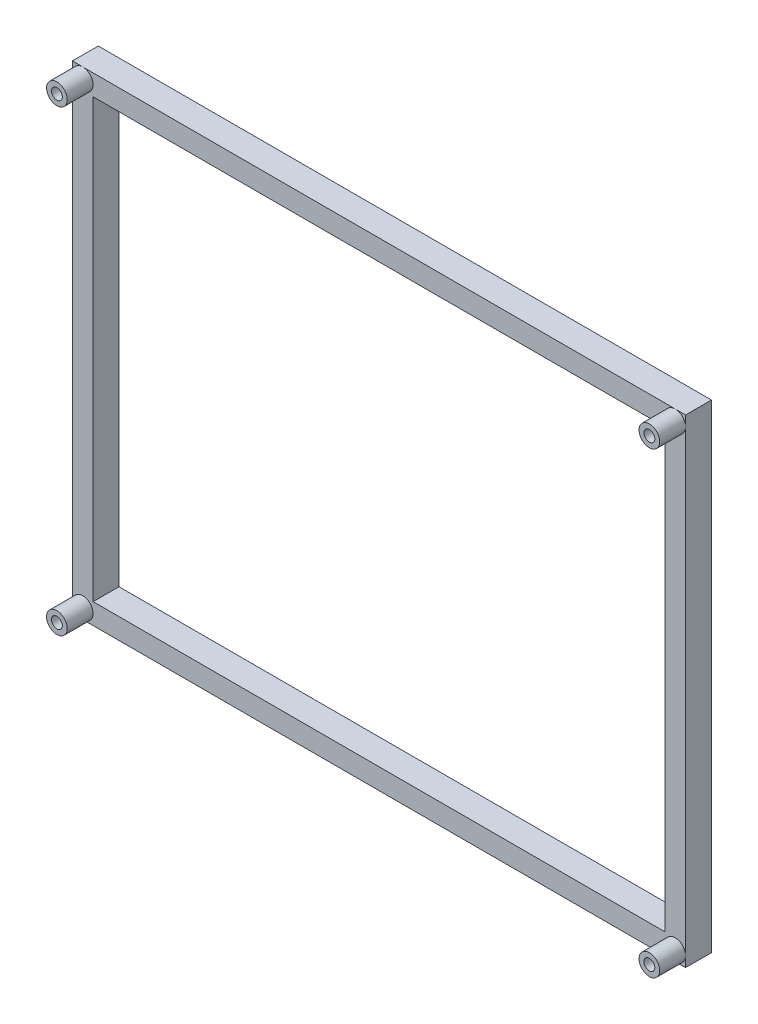
SolidWorks part; units mm, degrees
ref_plane "Front Plane" through (0, 0, 0) normal (0, 0, 1) x (1, 0, 0)
ref_plane "Top Plane" through (0, 0, 0) normal (0, 1, 0) x (1, 0, 0)
ref_plane "Right Plane" through (0, 0, 0) normal (1, 0, 0) x (0, 0, -1)
sketch "Sketch1" plane through (0, 0, 0) normal (0, 0, 1) x (1, 0, 0)
  line L1 (0, 0) -> (118.5, 0)
  line L2 (0, 0) -> (0, 92.5)
  line L3 (0, 92.5) -> (118.5, 92.5)
  line L4 (118.5, 0) -> (118.5, 92.5)
  line L5 (2, 90.5) -> (116.5, 90.5) construction
  line L6 (2, 90.5) -> (2, 2) construction
  line L7 (2, 2) -> (116.5, 2) construction
  line L8 (116.5, 90.5) -> (116.5, 2) construction
  line L9 (4, 88.5) -> (114.5, 88.5)
  line L10 (4, 88.5) -> (4, 4)
  line L11 (4, 4) -> (114.5, 4)
  line L12 (114.5, 88.5) -> (114.5, 4)
  point P13 (4, 46.25)
  point P14 (2, 46.25)
  point P15 (0, 46.25)
  point P16 (59.25, 4)
  point P17 (59.25, 2)
  point P18 (59.25, 0)
  dimension "D1" = 114.5
  dimension "D2" = 88.5
  dimension "D3" = 2
  dimension "D4" = 2
  dimension "D5" = 2
  dimension "D6" = 2
extrude "Boss-Extrude1" add sketch "Sketch1" against normal blind 5
sketch "Sketch2" plane through (0, 0, 0) normal (0, 0, 1) x (1, 0, 0)
  circle A0 centre (2, 90.5) radius 1.05
  circle A1 centre (116.5, 90.5) radius 1.05
  circle A2 centre (116.5, 2) radius 1.05
  circle A3 centre (2, 2) radius 1.05
  circle A4 centre (2, 90.5) radius 2
  circle A5 centre (116.5, 90.5) radius 2
  circle A6 centre (116.5, 2) radius 2
  circle A7 centre (2, 2) radius 2
  dimension "D1" = 2.1
  dimension "D2" = 4
extrude "Boss-Extrude2" add sketch "Sketch2" along normal blind 5
